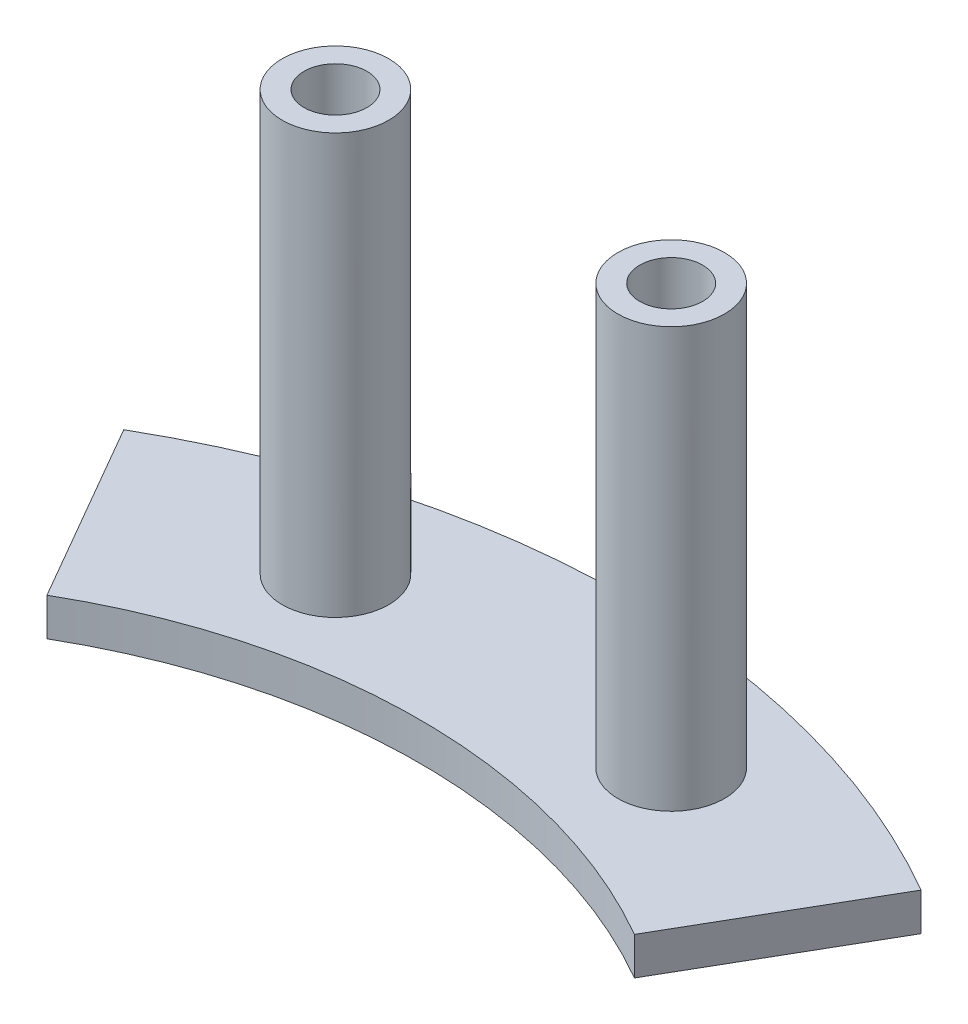
SolidWorks part; units mm, degrees
ref_plane "Front Plane" through (0, 0, 0) normal (0, 0, 1) x (1, 0, 0)
ref_plane "Top Plane" through (0, 0, 0) normal (0, 1, 0) x (1, 0, 0)
ref_plane "Right Plane" through (0, 0, 0) normal (1, 0, 0) x (0, 0, -1)
sketch "Sketch1" plane through (0, 0, 0) normal (0, 1, 0) x (1, 0, 0)
  line L0 (-14, 24.2487) -> (-19, 32.909) construction
  line L1 (14, 24.2487) -> (19, 32.909) construction
  line L2 (0, 0) -> (4, 0) construction
  line L3 (-19, 32.909) -> (-14, 24.2487)
  line L4 (19, 32.909) -> (14, 24.2487)
  circle A0 centre (0, 0) radius 28 construction
  circle A1 centre (0, 0) radius 38 construction
  arc A2 (-19, 32.909) -> (19, 32.909) centre (0, 0) cw
  arc A3 (-14, 24.2487) -> (14, 24.2487) centre (0, 0) cw
  arc A4 (-16.5, 28.5788) -> (16.5, 28.5788) centre (0, 0) cw construction
  dimension "D1" = 28
  dimension "D2" = 76
  dimension "D6" = 60
  dimension "D3" = 60
extrude "Boss-Extrude1" add sketch "Sketch1" along normal blind 1.8
sketch "Sketch2" plane through (0, 1.8, 0) normal (0, 1, 0) x (1, 0, 0)
  line L0 (-19, 32.909) -> (-14, 24.2487) construction
  line L2 (-8, 32) -> (8, 32) construction
  line L3 (0, 32) -> (0, 0) construction
  line L4 (14, 24.2487) -> (19, 32.909) construction
  arc A0 (-16.5, 28.5788) -> (16.5, 28.5788) centre (0, 0) cw construction
  circle A1 centre (-8, 32) radius 2.54
  circle A2 centre (8, 32) radius 2.54
  dimension "D1" = 5.08
  dimension "D2" = 8
  dimension "D3" = 32
extrude "Boss-Extrude2" add sketch "Sketch2" along normal blind 20
sketch "Sketch5" plane through (0, 21.8, 0) normal (0, 1, 0) x (1, 0, 0)
  circle A0 centre (-8, 32) radius 1.5
  circle A2 centre (8, 32) radius 1.5
  dimension "D1" = 3
extrude "Cut-Extrude1" cut sketch "Sketch5" against normal blind 3
